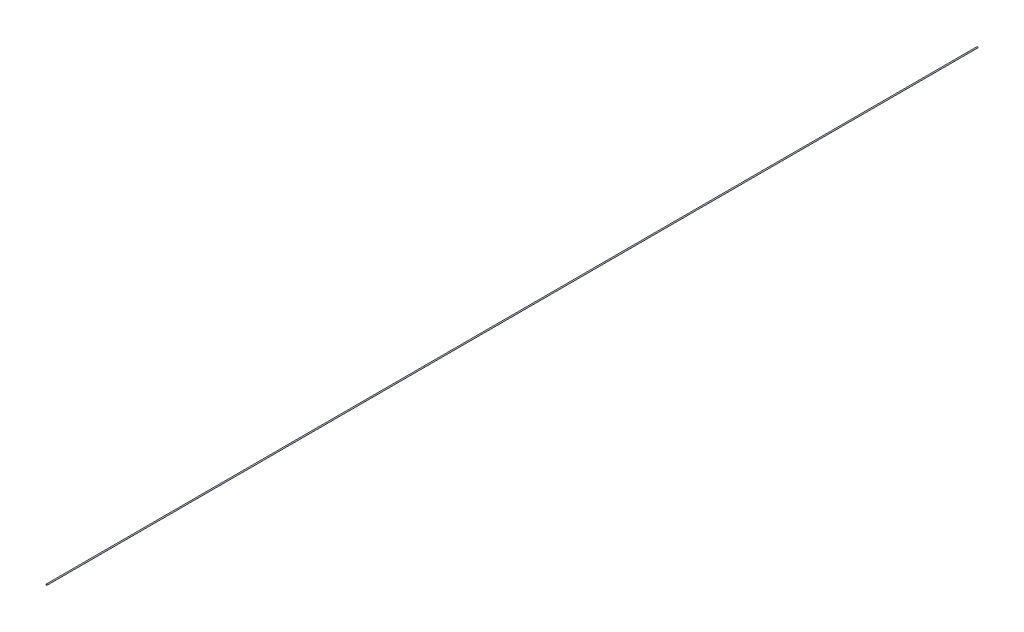
SolidWorks part; units mm, degrees
ref_plane "前视基准面" through (0, 0, 0) normal (0, 0, 1) x (1, 0, 0)
ref_plane "上视基准面" through (0, 0, 0) normal (0, 1, 0) x (1, 0, 0)
ref_plane "右视基准面" through (0, 0, 0) normal (1, 0, 0) x (0, 0, -1)
other "Configuration Table"
sketch "草图1" plane through (0, 0, 0) normal (0, 0, 1) x (1, 0, 0)
  circle A0 centre (0, 0) radius 3
  dimension "D1" = 6
extrude "凸台-拉伸1" add sketch "草图1" along normal blind 5000
